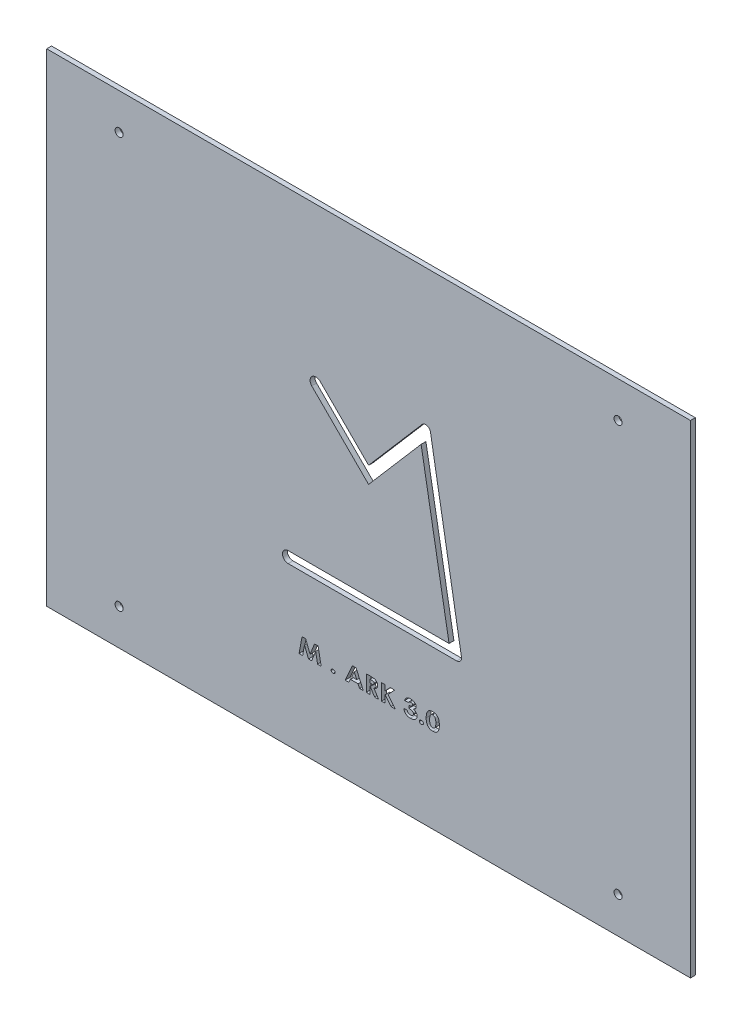
SolidWorks part; units mm, degrees
ref_plane "Front Plane" through (0, 0, 0) normal (0, 0, 1) x (1, 0, 0)
ref_plane "Top Plane" through (0, 0, 0) normal (0, 1, 0) x (1, 0, 0)
ref_plane "Right Plane" through (0, 0, 0) normal (1, 0, 0) x (0, 0, -1)
sketch "Sketch1" plane through (0, 0, 0) normal (0, 0, 1) x (1, 0, 0)
  line L1 (-200, -150) -> (200, -150)
  line L2 (-200, -150) -> (-200, 150)
  line L3 (-200, 150) -> (200, 150)
  line L4 (200, -150) -> (200, 150)
  line L5 (-200, -150) -> (200, 150) construction
  line L6 (-200, 150) -> (200, -150) construction
  point P0 (0, 0)
  dimension "D1" = 400
  dimension "D2" = 300
extrude "Boss-Extrude1" add sketch "Sketch1" along normal blind 3
sketch "Sketch2" plane through (0, 0, 3) normal (0, 0, 1) x (1, 0, 0)
  line L0 (0, -1000) -> (0, 49000) construction
  line L1 (-1000, 0) -> (49000, 0) construction
  line L2 (200, 150) -> (-200, 150) construction
  circle A0 centre (155, 127.5) radius 2.5
  circle A1 centre (-155, 127.5) radius 2.5
  circle A2 centre (-155, -127.5) radius 2.5
  circle A3 centre (155, -127.5) radius 2.5
  dimension "D2" = 22.5
  dimension "D3" = 5
  dimension "D1" = 155
extrude "Cut-Extrude1" cut sketch "Sketch2" against normal through all
sketch "Sketch3" plane through (0, 0, 3) normal (0, 0, 1) x (1, 0, 0)
  line L0 (0, -1108.5917) -> (0, 48891.4083) construction
  line L1 (-1206.6722, 0) -> (48793.3278, 0) construction
  line L2 (-50, -45) -> (50, -45)
  line L3 (50, -45) -> (32.6352, 53.4808)
  line L4 (32.6352, 53.4808) -> (0, 15.6001)
  line L5 (0, 15.6001) -> (-35.3553, 50.9554)
  line L6 (-50, -52) -> (54.767, -52)
  line L7 (57.7232, -48.4889) -> (38.4478, 62.9926)
  line L8 (33.2188, 64.4396) -> (0, 25.8815)
  line L9 (0, 25.8815) -> (-30.0237, 55.9052)
  line L10 (-200, -150) -> (200, -150) construction
  line L12 (200, -150) -> (200, 150) construction
  arc A0 (-50, -45) -> (-50, -52) centre (-50, -48.5) ccw
  arc A1 (-35.3553, 50.9554) -> (-30.0237, 55.9052) centre (-32.6895, 53.4303) cw
  arc A2 (57.7232, -48.4889) -> (54.767, -52) centre (54.767, -49) cw
  arc A3 (38.4478, 62.9926) -> (33.2188, 64.4396) centre (35.4917, 62.4815) ccw
  point P7 (0, -45)
  point P26 (0, 0)
  point P27 (0, 0)
  point P28 (0, 0)
  point P30 (-71.0962, -54.4902)
  dimension "D7" = 3
  dimension "D8" = 3
  dimension "D14" = 3.5
  dimension "D15" = 3.6375
  dimension "D1" = 80
  dimension "D2" = 100
  dimension "D3" = 100
  dimension "D4" = 45
  dimension "D5" = 50
  dimension "D6" = 45
  dimension "D9" = 98
  dimension "D10" = 145.233
  dimension "D11" = 48.5
  dimension "D12" = 6.7107
  dimension "D13" = 179.81
  dimension "D16" = 42.4599
  dimension "D17" = 32.6895
extrude "Cut-Extrude2" cut sketch "Sketch3" against normal through all
sketch "Sketch4" plane through (0, 0, 3) normal (0, 0, 1) x (1, 0, 0)
  line L0 (0, -1000) -> (0, 49000) construction
  line L1 (-52.3835, -97) -> (52.3835, -97) construction
  line L2 (-50, -52) -> (54.767, -52) construction
  text T0 "<b>M . ARK 3.0</b>" font "Century Gothic" height 10
  point P6 (0, -97)
  dimension "D1" = 45
extrude "Cut-Extrude3" cut sketch "Sketch4" against normal through all
